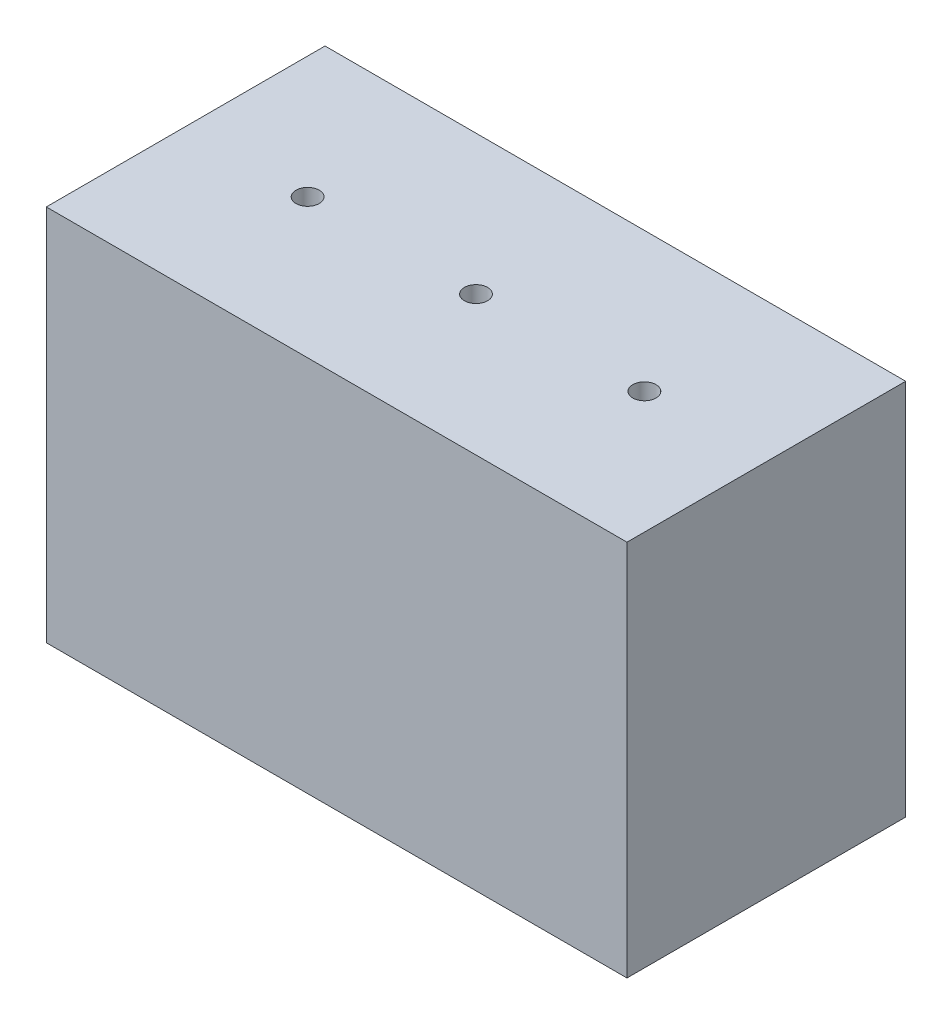
SolidWorks part; units mm, degrees
material "1060 Alloy"
ref_plane "Front Plane" through (0, 0, 0) normal (0, 0, 1) x (1, 0, 0)
ref_plane "Top Plane" through (0, 0, 0) normal (0, 1, 0) x (1, 0, 0)
ref_plane "Right Plane" through (0, 0, 0) normal (1, 0, 0) x (0, 0, -1)
sketch "Sketch2" plane through (0, 0, 0) normal (0, 1, 0) x (1, 0, 0)
  line L0 (-50, 0) -> (0, 0) construction
  line L1 (-50, 24) -> (50, 24)
  line L2 (-50, 24) -> (-50, -24)
  line L3 (-50, -24) -> (50, -24)
  line L4 (50, 24) -> (50, -24)
  line L5 (-50, 24) -> (50, -24) construction
  line L6 (-50, -24) -> (50, 24) construction
  line L7 (0, 0) -> (50, 0) construction
  circle A3 centre (-29, 0) radius 2
  circle A4 centre (0, 0) radius 2
  circle A5 centre (29, 0) radius 2
  point P0 (0, 0)
  dimension "D3" = 4
  dimension "D4" = 4
  dimension "D5" = 29
  dimension "D6" = 29
  dimension "D7" = 21
  dimension "D8" = 21
  dimension "D1" = 100
  dimension "D2" = 48
extrude "Boss-Extrude1" add sketch "Sketch2" against normal blind 65
